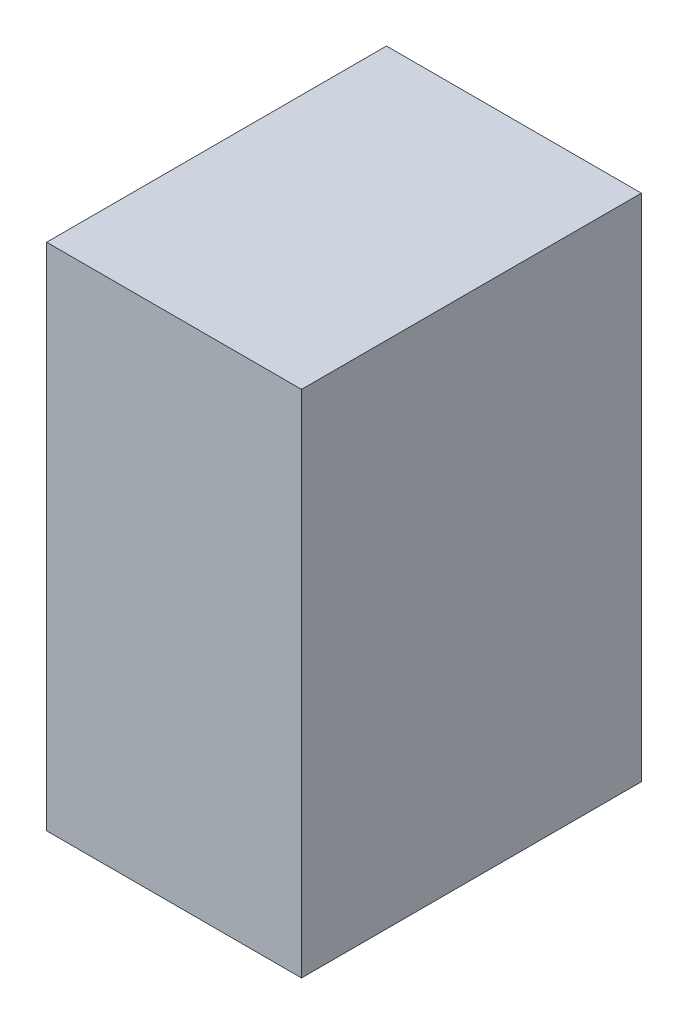
SolidWorks part; units mm, degrees
material "Balsa"
ref_plane "Front Plane" through (0, 0, 0) normal (0, 0, 1) x (1, 0, 0)
ref_plane "Top Plane" through (0, 0, 0) normal (0, 1, 0) x (1, 0, 0)
ref_plane "Right Plane" through (0, 0, 0) normal (1, 0, 0) x (0, 0, -1)
sketch "Sketch1" plane through (0, 0, 0) normal (0, 1, 0) x (1, 0, 0)
  line L0 (-37.5, -50) -> (37.5, 50) construction
  line L1 (-37.5, 50) -> (37.5, 50)
  line L2 (-37.5, 50) -> (-37.5, -50)
  line L3 (-37.5, -50) -> (37.5, -50)
  line L4 (37.5, 50) -> (37.5, -50)
  dimension "D1" = 75
  dimension "D2" = 100
extrude "Extrude1" add sketch "Sketch1" along normal blind 150
